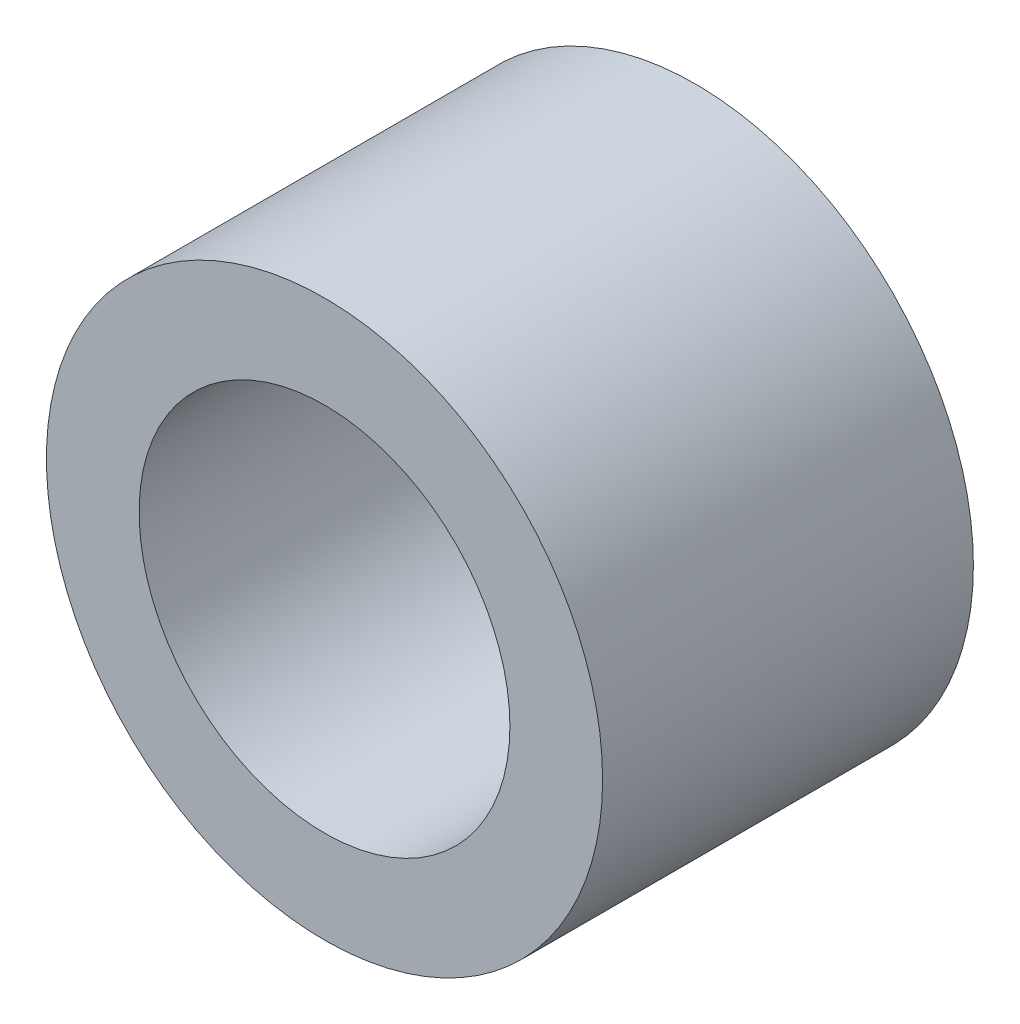
SolidWorks part; units mm, degrees
ref_plane "前视基准面" through (0, 0, 0) normal (0, 0, 1) x (1, 0, 0)
ref_plane "上视基准面" through (0, 0, 0) normal (0, 1, 0) x (1, 0, 0)
ref_plane "右视基准面" through (0, 0, 0) normal (1, 0, 0) x (0, 0, -1)
other "Configuration Table"
sketch "草图1" plane through (0, 0, 0) normal (0, 0, 1) x (1, 0, 0)
  circle A0 centre (0, 0) radius 4.5
  circle A1 centre (0, 0) radius 3
  dimension "D1" = 9
  dimension "D2" = 6
extrude "凸台-拉伸1" add sketch "草图1" along normal blind 6
